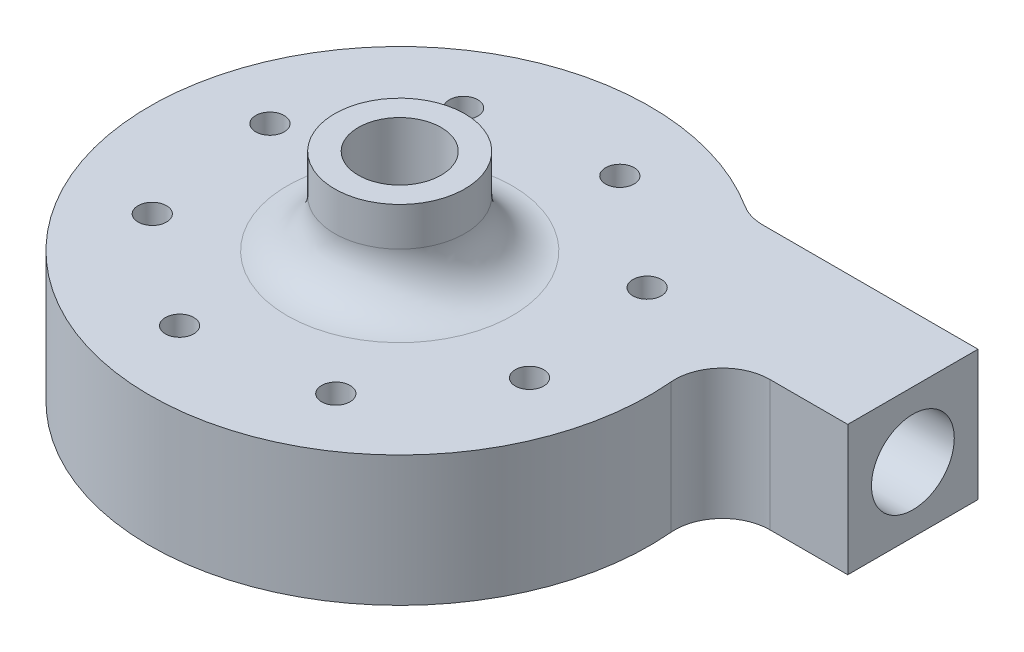
SolidWorks part; units mm, degrees
material "1060 Alloy"
ref_plane "Front" through (0, 0, 0) normal (0, 0, 1) x (1, 0, 0)
ref_plane "Top" through (0, 0, 0) normal (0, 1, 0) x (1, 0, 0)
ref_plane "Right" through (0, 0, 0) normal (1, 0, 0) x (0, 0, -1)
sketch "Sketch1" plane through (0, 0, 0) normal (0, 1, 0) x (1, 0, 0)
  line L0 (0, 0) -> (2.6693, 30.5101) construction
  line L1 (2.6693, 30.5101) -> (60.9409, 35.6082) construction
  line L2 (9.0461, 29.2602) -> (60.9409, 29.2602) construction
  line L3 (14.512, 26.9702) -> (60.9409, 22.9082) construction
  line L4 (0, 0) -> (52.5493, -4.5975) construction
  line L5 (14.512, 31.5462) -> (14.512, 29.2602) construction
  line L6 (14.512, 29.2602) -> (14.512, 26.9702) construction
  line L7 (60.9409, 29.2602) -> (60.9409, 35.6082) construction
  line L8 (60.9409, 29.2602) -> (60.9409, 22.9082) construction
  line L9 (78.9409, 29.2602) -> (78.9409, 42.9915)
  line L10 (78.9409, 37.9915) -> (60.9409, 37.9915) construction
  line L11 (78.9409, 37.9915) -> (78.9409, 20.529) construction
  line L12 (78.9409, 20.529) -> (60.9409, 20.529) construction
  line L13 (60.9409, 37.9915) -> (60.9409, 20.529) construction
  line L14 (78.9409, 42.9915) -> (33.6075, 42.9915)
  line L15 (78.9409, 29.2602) -> (78.9409, 15.529)
  line L16 (78.9409, 15.529) -> (62.5059, 15.529)
  arc A0 (28.2517, 44.5466) -> (52.5448, 4.6479) centre (0, 0) ccw
  circle A1 centre (0, 0) radius 30.6267 construction
  arc A2 (62.5059, 15.529) -> (52.5448, 4.6479) centre (62.5059, 5.529) ccw
  arc A3 (33.6075, 42.9915) -> (28.2517, 44.5466) centre (33.6075, 52.9915) cw
  dimension "D1" = 105.5
  dimension "D2" = 61.2534
  dimension "D13" = 10
  dimension "D4" = 2.286
  dimension "D3" = 2.29
  dimension "D5" = 5
  dimension "D6" = 5
  dimension "D7" = 5
  dimension "D8" = 12.7
  dimension "D9" = 17.4625
  dimension "D10" = 18
  dimension "D11" = 5
  dimension "D12" = 5
extrude "main body" add sketch "Sketch1" along normal blind 27.4625
ref_plane "body midsection" through (0, 13.7313, 0) normal (0, 1, 0) x (1, 0, 0)
sketch "Sketch2" plane through (0, 0, 0) normal (0, 0, 1) x (1, 0, 0)
  line L0 (0, 27.4625) -> (0, 0) construction
  line L1 (52.75, 27.4625) -> (-52.75, 27.4625) construction
  line L2 (0, 27.4625) -> (5.4102, 27.4625)
  line L3 (0, 10.3295) -> (30.6267, 10.3295) construction
  line L4 (30.6267, 14.0995) -> (5.4102, 20.623)
  line L5 (5.4102, 27.4625) -> (5.4102, 20.623)
  line L7 (30.6267, 14.0995) -> (30.6267, 13.7313)
  line L8 (58.025, 13.7313) -> (-58.025, 13.7313) construction
  line L9 (30.6267, 13.7313) -> (30.6267, 0)
  line L10 (-52.75, 0) -> (52.75, 0) construction
  line L11 (30.6267, 0) -> (0, 0)
  line L12 (0, 0) -> (0, 27.4625)
  line L14 (0, 13.7313) -> (26.6319, 13.7313) construction
  line L15 (26.6319, 13.7313) -> (26.6319, 15.1329) construction
  dimension "D1" = 30.6267
  dimension "D3" = 26.6319
  dimension "D4" = 1.4017
  dimension "D5" = 5.4102
  dimension "D2" = 4.8034
  dimension "D6" = 10.2934
revolve "main chamber" cut sketch "Sketch2" angle 360 about L12
sketch "Sketch4" plane through (0, 0, 0) normal (0, 0, 1) x (1, 0, 0)
  line L0 (5.4102, 27.4625) -> (5.4102, 30.623)
  line L2 (5.4102, 30.623) -> (8.7313, 30.623)
  line L3 (8.7313, 30.623) -> (8.7313, 45.623)
  line L4 (8.7313, 45.623) -> (13.7313, 45.623)
  line L5 (13.7313, 45.623) -> (13.7313, 37.4625)
  line L7 (0, 0) -> (0, 49.2593) construction
  line L8 (52.75, 0) -> (-52.75, 0) construction
  line L9 (5.4102, 20.623) -> (-5.4102, 20.623) construction
  line L10 (5.4102, 27.4625) -> (23.7313, 27.4625)
  arc A0 (13.7313, 37.4625) -> (23.7313, 27.4625) centre (23.7313, 37.4625) ccw
  dimension "D5" = 10
  dimension "D1" = 10
  dimension "D2" = 8.7313
  dimension "D3" = 5
  dimension "D4" = 15
revolve "inlet" add sketch "Sketch4" angle 360 about L7
sketch "Sketch3" plane through (0, 13.7313, 0) normal (0, 1, 0) x (1, 0, 0)
  line L0 (2.6693, 30.5101) -> (60.9409, 35.6082)
  line L2 (60.9409, 29.2602) -> (2.5599, 29.2602)
  line L3 (0, 0) -> (2.6693, 30.5101) construction
  line L4 (2.5599, 29.2602) -> (2.6693, 30.5101)
  line L5 (60.9409, 35.6082) -> (60.9409, 37.9915)
  line L6 (60.9409, 37.9915) -> (78.9409, 37.9915)
  line L7 (78.9409, 37.9915) -> (78.9409, 29.2602)
  line L8 (78.9409, 29.2602) -> (60.9409, 29.2602)
revolve "expansion cone and outlet" cut sketch "Sketch3" angle 360 about L2
sketch "Sketch5" plane through (0, 27.4625, 0) normal (0, 1, 0) x (1, 0, 0)
  line L0 (14.5032, 26.975) -> (60.9409, 22.9122) construction
  circle A0 centre (0, 0) radius 38.1 construction
  circle A1 centre (32.8208, 19.3495) radius 3
  dimension "D1" = 76.2
  dimension "D2" = 6
  dimension "D3" = 6
extrude "bolts" cut sketch "Sketch5" against normal blind 40
pattern_circular "CirPattern1" count 8 over 360 about axis through (0, 0, 0) along (0, 1, 0) of "bolts"
ref_plane "exit axial plane" through (0, 0, -29.2602) normal (0, 0, -1) x (-1, 0, 0)
equation "\"bearing OD\"= 30mm"
equation "\"bearing ID\"= 10mm"
equation "\"bearing depth\"= 9mm"
equation "\"bearing outer race thickness\"= 1mm"
equation "\"bearing inner race thickness\"= 1mm"
equation "\"bearing bore\"= \"bearing depth\" + 1mm"
equation "\"small seal OD\"= 20mm"
equation "\"small seal ID\"= 8mm"
equation "\"small seal depth\"= 8.3mm"
equation "\"small seal bore\"= \"small seal depth\" + 1mm"
equation "\"big seal OD\"= 27mm"
equation "\"big seal ID\"= 15mm"
equation "\"big seal depth\"= 8.3mm"
equation "\"big seal bore\"= \"big seal depth\" + 1mm"
equation "\"z\"= 8 \t\t'number of blades"
equation "\"de\"= 0.426in \t\t'entrance eye diameter"
equation "\"d2\"= 2.097in \t\t'outer diameter of the impeller "
equation "\"d_exit\"= 0.18in \t'volute throat aka D4"
equation "\"theta\"= 15"
equation "\"b2\"= .071in\t\t\t\t\t\t\t'tip height from disc surface at d2"
equation "\"b1\"= \"b2\" + (\"d2\"/2 - \"de\"/2)*sin(\"theta\")\t\t\t'tip height from disc surface at inlet eye"
equation "\"s\"= ( 1/\"z\")*(3.14*\"de\" - (3.14*(\"de\"^2) / (4*(\"b1\"))))\t'thickness of blades, calculated from area"
equation "\"s_opening\"= (3.14*\"de\" - \"z\"*\"s\")/\"z\"\t\t\t\t'ideal gap between blades, calculated from area"
equation "\"area_eye\"=3.14*(\"de\"^2)/4\t\t\t\t\t'eye area"
equation "\"single_channel_area\"=\"s_opening\"*\"b1\"\t\t\t\t'ideal area between two blades"
equation "\"minimum channel width\"= \"s_opening\"\t\t\t\t\t\t\t'minimum s, set this to a bit size for milling or to s_opening for DMLS"
equation "\"inlet area before cut\"= \"minimum channel width\" * (\"z\") * \"b1\"\t\t\t'if minimum channel width>s_opening, this is larger than area_eye"
equation "\"area to cut\"= \"inlet area before cut\" - \"area_eye\"\t\t\t\t\t'amount of extra area\t\t\t\t\t"
equation "\"height to cut\"= \"area to cut\" / ((\"z\")* \"minimum channel width\")+ .0001in\t\t'the 0.0001 in cut is to avoid errors in model"
equation "\"final impeller center height\"= \"impeller base thickness\" + \"b1\" - \"height to cut\"\t'corrected height so that sum of channel areas equals eye area"
equation "\"impeller upper clearance\"= .5mm"
equation "\"impeller horizontal clearance\"= (\"d2\"*1.15 - \"d2\")/2 \t\t\t\t\t'clearance based on D2-D3 ratio for circular volute, ranges 1.15 to 1.2"
equation "\"impeller bottom clearance\"= .5mm"
equation "\"impeller base thickness\"= 2mm"
equation "\"impeller dowel diameter\"= 2mm"
equation "\"impeller bolt head diameter\"= 7.5mm"
equation "\"impeller bolt head depth\"= 4mm"
equation "\"impeller bolt stop depth\"= 3mm"
equation "\"impeller bolt bore\"= 4mm"
equation "\"impeller shaft bore depth\"= 20mm"
equation "\"impeller shaft bore\"= 8mm"
equation "\"impeller boss depth\"= \"impeller shaft bore depth\"+\"impeller bolt stop depth\"+\"impeller bolt head depth\"-\"impeller base thickness\""
equation "\"impeller boss diameter\"= \"big seal ID\""
equation "\"impeller dowel length\"= 2mm*2 + \"impeller shaft bore\""
equation "\"coupler motor shaft hole ID\"= 8mm"
equation "\"coupler OD\"= 17mm"
equation "\"coupler length\"= 25mm"
equation "\"motor OD\"= 64mm"
equation "\"motor shaft diameter\"= 8mm"
equation "\"motor shaft pride\"= 32mm"
equation "\"motor to bearing plate distance\"= \"motor shaft pride\" + 2mm +\"coupler length\"/2"
equation "\"square plate bolt bore\"= 8mm"
equation "\"square plate bolt head diameter\"= 13.5mm"
equation "\"square plate bolt head depth\"= 8mm"
equation "\"square plate bolt pattern diameter\"= \"motor OD\" + \"square plate bolt head diameter\" + 4mm"
equation "\"motor mount center bore\"= \"coupler OD\"+ 4mm"
equation "\"motor mount post radius\"= ( 3 * \"square plate bolt bore\" ) / 2"
equation "\"motor mount m4 screw hole diameter\"= 4mm"
equation "\"motor mount m4 head diameter\"= 7.25mm"
equation "\"motor mount m4 head depth\"= 4mm"
equation "\"motor mount m4 pattern diamater\"= 30mm"
equation "\"motor mount plate thickness\"= 8mm + \"motor mount m4 head depth\""
equation "\"bearing plate stop ID\"= \"bearing OD\" - 4mm"
equation "\"bearing plate stop depth\"= 3mm"
equation "\"bearing plate thickness\"= \"bearing bore\" + \"bearing plate stop depth\" + \"shaft bearing stop length\""
equation "\"small seal plate lip depth\"= 2mm"
equation "\"small seal plate lip ID\"= \"small seal OD\" - 3mm"
equation "\"small seal plate thickness\"= \"small seal plate lip depth\" + \"small seal bore\""
equation "\"shaft coupler section diameter\"= 8mm"
equation "\"shaft coupler section length\"= \"motor to bearing plate distance\" - \"motor shaft pride\" - 2mm"
equation "\"shaft bearing section diameter\"= \"bearing ID\""
equation "\"shaft bearing section length\"= \"bearing plate stop depth\" + \"bearing depth\""
equation "\"shaft bearing stop diameter\"= \"bearing ID\" + 4mm"
equation "\"shaft bearing stop length\"= 3mm"
equation "\"shaft small seal section diameter\"= \"small seal ID\""
equation "\"shaft small seal section length\"= \"small seal plate thickness\" + 1mm"
equation "\"big seal plate thickness\"= \"big seal plate pressure tap diameter\" + 2*\"big seal plate pressure tap grip\""
equation "\"big seal plate lip ID\"= \"big seal OD\" - 3mm"
equation "\"big seal plate riser\"= \"impeller housing thickness\"/2 - \"b2\"/2 - \"impeller base thickness\" - \t\"impeller bottom clearance\"\t\t\t'this offsets the gap under the housing"
equation "\"big seal plate pressure hole diameter\"= .125in\t'this is 1/8 drill "
equation "\"big seal plate pressure tap diameter\"= .328125in \t'this is 21/64 drill for a 1/8 ANPT tap"
equation "\"big seal plate pressure tap grip\"= 4mm\t\t'this is the area around the tap so it doesn't crack"
equation "\"big seal plate pressure tap depth\"= 12"
equation "\"impeller cavity center height\"= \"impeller bottom clearance\" + \"impeller upper clearance\" + \"final impeller center height\""
equation "\"impeller cavity diameter\"= 2 * \"impeller horizontal clearance\" + \"d2\" \t\t\t\t\t\t\t\t\t'called D3 analytically"
equation "\"impeller cavity outer height\"= \"impeller bottom clearance\" + \"impeller upper clearance\" + \"impeller base thickness\" + \"b2\" \t\t'this is height at impeller diameter d2, not at d3"
equation "\"impeller housing thickness\"= \"impeller housing exit threaded diameter\" + 2*\"impeller housing outlet grip\""
equation "\"impeller housing diameter\"= \"square plate bolt pattern diameter\" + 2*\"motor mount post radius\""
equation "\"impeller housing bolt count\"= 8"
equation "\"impeller housing bolt diameter\"= 6mm"
equation "\"impeller housing bolt pattern diameter\"= 3in"
equation "\"impeller housing threaded inlet diameter\"= 0.6875in \t\t'this is the 11/16 drill size for 1/2 npt fitting"
equation "\"impeller housing threaded inlet depth\"= 15mm"
equation "\"impeller housing exit threaded diameter\"= 0.6875in \t\t'this is the 11/16 drill size for 1/2 npt fitting"
equation "\"impeller housing exit threaded depth\"= 18mm"
equation "\"impeller housing diffuser conical angle\"=10"
equation "\"impeller housing diffuser tangent angle\"=5"
equation "\"impeller housing diffuser final diameter\"= .5in"
equation "\"impeller housing outlet grip\"= 5mm"
equation "\"D1@Sketch1\"=\"impeller housing diameter\""
equation "\"D2@Sketch1\"=\"impeller cavity diameter\""
equation "\"D4@Sketch1\"=\"d_exit\"/2"
equation "\"D5@Sketch1\"=\"impeller housing diffuser tangent angle\""
equation "\"D6@Sketch1\"=\"impeller housing diffuser conical angle\"/2"
equation "\"D7@Sketch1\"=\"impeller housing diffuser conical angle\"/2"
equation "\"D8@Sketch1\"=\"impeller housing diffuser final diameter\""
equation "\"D9@Sketch1\"=\"impeller housing exit threaded diameter\""
equation "\"D10@Sketch1\"=\"impeller housing exit threaded depth\""
equation "\"D11@Sketch1\"=\"impeller housing outlet grip\""
equation "\"D12@Sketch1\"=\"impeller housing outlet grip\""
equation "\"D1@main body\" = \"impeller housing thickness\""
equation "\"D1@Sketch2\"=\"impeller cavity diameter\"/2"
equation "\"D3@Sketch2\"=\"d2\"/2"
equation "\"D4@Sketch2\"=\"b2\"/2 + \"impeller upper clearance\""
equation "\"D2@Sketch2\"=\"impeller cavity outer height\""
equation "\"D5@Sketch2\"=\"de\"/2"
equation "\"D6@Sketch2\"=\"final impeller center height\" + \"impeller bottom clearance\" + \"impeller upper clearance\""
equation "\"de_length\"= 10mm\t'entrance eye consistent length"
equation "\"D2@Sketch4\"=\"impeller housing threaded inlet diameter\"/2"
equation "\"D3@Sketch4\"=\"impeller housing outlet grip\""
equation "\"D4@Sketch4\"=\"impeller housing threaded inlet depth\""
equation "\"D1@Sketch5\"=\"impeller housing bolt pattern diameter\""
equation "\"D2@Sketch5\"=\"impeller housing bolt diameter\""
equation "\"D3@Sketch5\"=\"impeller housing bolt diameter\""
equation "\"D1@CirPattern1\"=\"impeller housing bolt count\""
